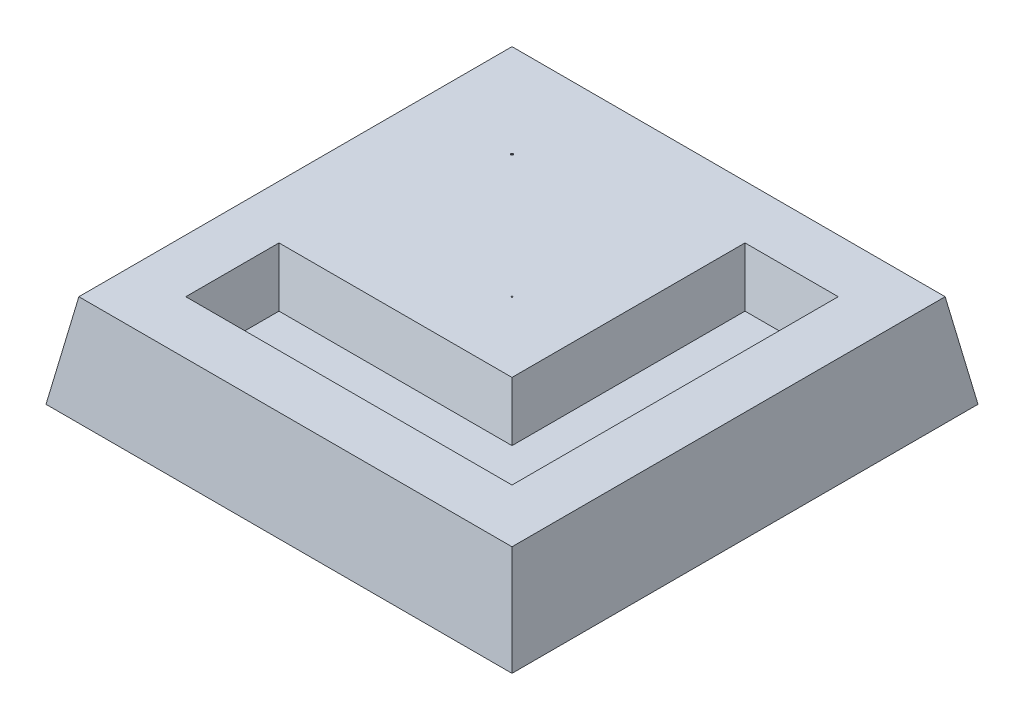
SolidWorks part; units mm, degrees
material "AISI 304"
ref_plane "Front Plane" through (0, 0, 0) normal (0, 0, 1) x (1, 0, 0)
ref_plane "Top Plane" through (0, 0, 0) normal (0, 1, 0) x (1, 0, 0)
ref_plane "Right Plane" through (0, 0, 0) normal (1, 0, 0) x (0, 0, -1)
sketch "Sketch2" plane through (0, 0, 0) normal (0, 1, 0) x (1, 0, 0)
  line L1 (-1270, -1270) -> (1270, -1270)
  line L2 (-1270, -1270) -> (-1270, 1270)
  line L3 (-1270, 1270) -> (1270, 1270)
  line L4 (1270, -1270) -> (1270, 1270)
  line L5 (-1270, -1270) -> (1270, 1270) construction
  line L6 (-1270, 1270) -> (1270, -1270) construction
  point P0 (0, 0)
  dimension "D1" = 2540
  dimension "D2" = 2540
extrude "Boss-Extrude1" add sketch "Sketch2" along normal blind 508
sketch "Sketch3" plane through (0, 508, 0) normal (0, 1, 0) x (1, 0, 0)
  line L0 (381, 889) -> (381, -381)
  line L1 (381, -381) -> (-889, -381)
  line L2 (-889, -381) -> (-889, -889)
  line L3 (-889, -889) -> (889, -889)
  line L4 (889, -889) -> (889, 889)
  line L5 (889, 889) -> (381, 889)
  line L7 (1270, -1270) -> (1270, 1270) construction
  line L9 (-1270, -1270) -> (1270, -1270) construction
  dimension "D1" = 1778
  dimension "D2" = 381
  dimension "D3" = 508
  dimension "D4" = 1270
  dimension "D5" = 1270
  dimension "D6" = 381
extrude "Cut-Extrude2" cut sketch "Sketch3" against normal blind 254
draft "Draft3" type of draft neutral plane draft angle 15 faces to draft 6 face at (381, 381, -254) face at (-254, 381, 381) face at (-889, 381, 635) face at (0, 381, 889) face at (889, 381, 0) face at (635, 381, -889) neutral plane through (0, 508, 0) neutral plane normal (0, 1, 0) parameters "D1"=15
draft "Draft4" type of draft neutral plane draft angle 10 faces to draft 4 face at (-1270, 254, 0) face at (0, 254, -1270) face at (1270, 254, 0) face at (0, 254, 1270) neutral plane through (0, 0, 0) neutral plane normal (0, -1, 0) reverse direction yes parameters "D1"=10
hole_wizard "CBORE for M5 Hex Head Cap Screw1" positions "Sketch4" profile "Sketch5" counterbore size "M5" standard "ANSI Metric" end condition through all
sketch "Sketch4" plane through (0, 508, 0) normal (0, 1, 0) x (1, 0, 0)
  line L0 (-1180.4259, 1180.4259) -> (-1180.4259, -1180.4259) construction
  line L1 (1180.4259, 1180.4259) -> (-1180.4259, 1180.4259) construction
  point P0 (-672.4259, 672.4259)
  dimension "D1" = 508
  dimension "D2" = 508
sketch "Sketch5" plane through (-672.4259, 508, -672.4259) normal (1, 0, 0) x (0, 0, 1)
  line L0 (0, 0) -> (0, 508)
  line L1 (0, 508) -> (2.9, 508)
  line L3 (2.9, 508) -> (2.9, 5.65)
  line L4 (2.9, 5.65) -> (6.12, 5.65)
  line L5 (6.12, 5.65) -> (6.12, 0)
  line L7 (6.12, 0) -> (0, 0)
  line L11 (0, -6.35) -> (0, 107.95) construction
  dimension "Thru Hole Dia." = 5.8
  dimension "Thru Hole Depth" = 508
  dimension "C'Bore Dia." = 12.24
  dimension "C'Bore Depth" = 5.65
hole_wizard "Ø8.0mm Dowel Hole1" positions "Sketch6" profile "Sketch7" hole size "Ø8.0" standard "ANSI Metric" end condition through all
sketch "Sketch6" plane through (0, 508, 0) normal (0, 1, 0) x (1, 0, 0)
  point P0 (0, 0)
sketch "Sketch7" plane through (0, 508, 0) normal (1, 0, 0) x (0, 0, 1)
  line L0 (0, 0) -> (0, 508)
  line L1 (0, 508) -> (4, 508)
  line L2 (4, 508) -> (4, 0)
  line L5 (4, 0) -> (0, 0)
  line L11 (0, -6.35) -> (0, 107.95) construction
  dimension "Thru Hole Dia." = 8
  dimension "Thru Hole Depth" = 508
equation "\"D2@Sketch2\"=\"D1@Sketch2\""
equation "\"D5@Sketch3\"=\"D4@Sketch3\""
equation "\"D6@Sketch3\"=\"D2@Sketch3\""
